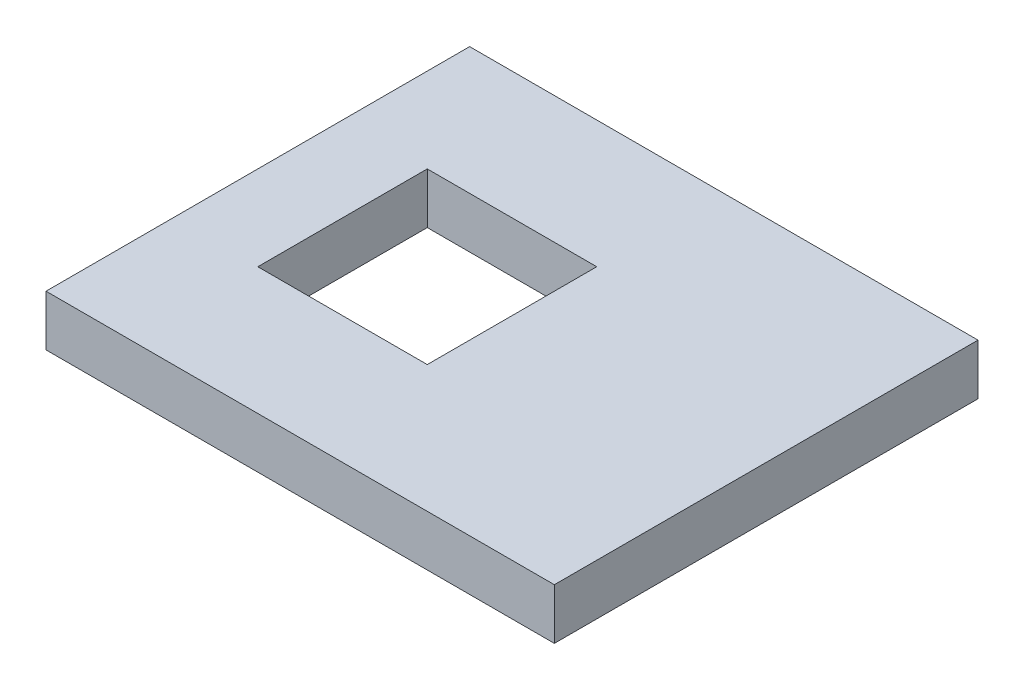
SolidWorks part; units mm, degrees
material "PVC Rigid"
ref_plane "Front Plane" through (0, 0, 0) normal (0, 0, 1) x (1, 0, 0)
ref_plane "Top Plane" through (0, 0, 0) normal (0, 1, 0) x (1, 0, 0)
ref_plane "Right Plane" through (0, 0, 0) normal (1, 0, 0) x (0, 0, -1)
sketch "Sketch6" plane through (0, 0, 0) normal (0, 1, 0) x (1, 0, 0)
  line L1 (-15.9091, 12.5) -> (14.0909, 12.5)
  line L2 (-15.9091, 12.5) -> (-15.9091, -12.5)
  line L3 (-15.9091, -12.5) -> (14.0909, -12.5)
  line L4 (14.0909, 12.5) -> (14.0909, -12.5)
  dimension "D1" = 25
  dimension "D2" = 30
extrude "Boss-Extrude6" add sketch "Sketch6" along normal blind 3
sketch "Sketch8" plane through (0, 3, 0) normal (0, 1, 0) x (1, 0, 0)
  line L1 (-10.9091, 5) -> (-0.9091, 5)
  line L2 (-10.9091, 5) -> (-10.9091, -5)
  line L3 (-10.9091, -5) -> (-0.9091, -5)
  line L4 (-0.9091, 5) -> (-0.9091, -5)
  line L7 (-15.9091, 12.5) -> (14.0909, 12.5) construction
  point P4 (-10.9091, 0)
  point P8 (-34.2525, 39.3441)
  point P9 (-35.0717, 35.0728)
  point P10 (-32.2278, 42.7585)
  point P11 (-0.9091, 0)
  point P14 (-0.9091, 12.5)
  dimension "D1" = 10
  dimension "D2" = 10
extrude "Cut-Extrude1" cut sketch "Sketch8" against normal through all
